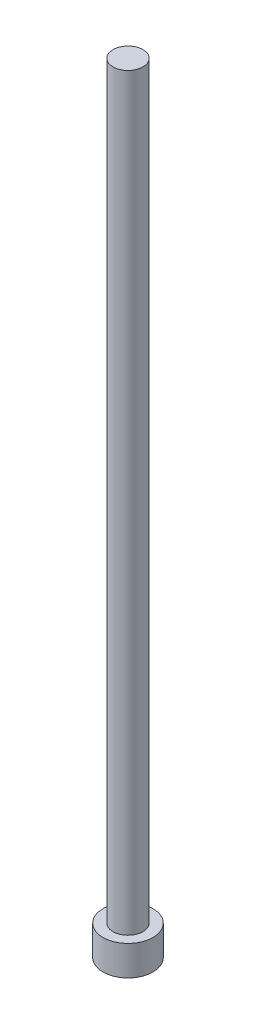
SolidWorks part; units mm, degrees
ref_plane "Front Plane" through (0, 0, 0) normal (0, 0, 1) x (1, 0, 0)
ref_plane "Top Plane" through (0, 0, 0) normal (0, 1, 0) x (1, 0, 0)
ref_plane "Right Plane" through (0, 0, 0) normal (1, 0, 0) x (0, 0, -1)
sketch "Sketch1" plane through (0, 0, 0) normal (0, 1, 0) x (1, 0, 0)
  circle A0 centre (0, 0) radius 2.5
  dimension "D1" = 5
extrude "Boss-Extrude1" add sketch "Sketch1" along normal blind 3
sketch "Sketch2" plane through (0, 3, 0) normal (0, 1, 0) x (1, 0, 0)
  circle A0 centre (0, 0) radius 1.5
  dimension "D1" = 3
extrude "Boss-Extrude2" add sketch "Sketch2" along normal blind 75
